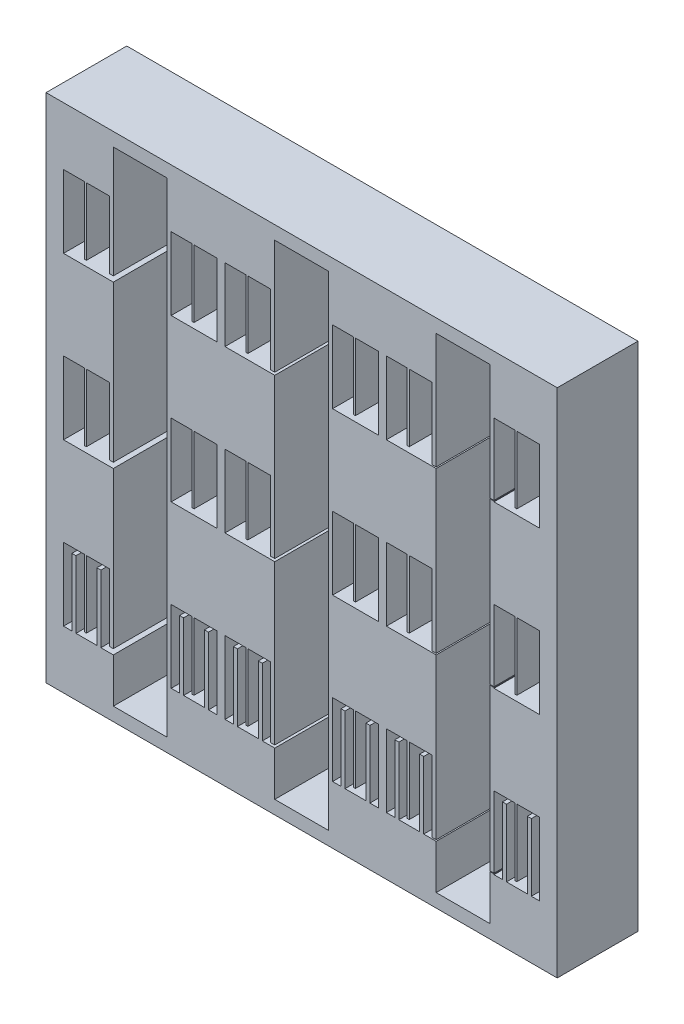
SolidWorks part; units mm, degrees
material "ABS"
ref_plane "Front Plane" through (0, 0, 0) normal (0, 0, 1) x (1, 0, 0)
ref_plane "Top Plane" through (0, 0, 0) normal (0, 1, 0) x (1, 0, 0)
ref_plane "Right Plane" through (0, 0, 0) normal (1, 0, 0) x (0, 0, -1)
sketch "Sketch1" plane through (0, 0, 0) normal (0, 0, 1) x (1, 0, 0)
  line L1 (-95, -95) -> (95, -95)
  line L2 (-95, -95) -> (-95, 95)
  line L3 (-95, 95) -> (95, 95)
  line L4 (95, -95) -> (95, 95)
  line L5 (0, 95) -> (0, -95) construction
  line L6 (-95, 0) -> (95, 0) construction
  point P16 (0, 0)
extrude "Boss-Extrude1" add sketch "Sketch1" against normal blind 30
sketch "Sketch2" plane through (0, 0, 0) normal (0, 0, 1) x (1, 0, 0)
  line L1 (-70, -90) -> (-50, -90)
  line L2 (-70, -90) -> (-70, 90)
  line L3 (-70, 90) -> (-50, 90)
  line L4 (-50, -90) -> (-50, 90)
  line L5 (-60, 90) -> (-60, -90) construction
  line L6 (-70, 0) -> (-50, 0) construction
  line L7 (-10, -90) -> (10, -90)
  line L8 (-10, -90) -> (-10, 90)
  line L9 (-10, 90) -> (10, 90)
  line L10 (10, -90) -> (10, 90)
  line L11 (0, 90) -> (0, -90) construction
  line L12 (-10, 0) -> (10, 0) construction
  line L13 (50, -90) -> (70, -90)
  line L14 (50, -90) -> (50, 90)
  line L15 (50, 90) -> (70, 90)
  line L16 (70, -90) -> (70, 90)
  line L17 (60, 90) -> (60, -90) construction
  line L18 (50, 0) -> (70, 0) construction
  point P16 (-60, 0)
  point P25 (0, 0)
  point P34 (60, 0)
extrude "Cut-Extrude1" cut sketch "Sketch2" against normal through all
sketch "Sketch3" plane through (0, 0, 0) normal (0, 0, 1) x (1, 0, 0)
  line L1 (-88.5, -73.5) -> (-71.5, -73.5)
  line L2 (-88.5, -73.5) -> (-88.5, -46.5)
  line L3 (-88.5, -46.5) -> (-71.5, -46.5)
  line L4 (-71.5, -73.5) -> (-71.5, -46.5)
  line L5 (-80, -46.5) -> (-80, -73.5) construction
  line L6 (-88.5, -60) -> (-71.5, -60) construction
  line L7 (-48.5, -73.5) -> (-31.5, -73.5)
  line L8 (-48.5, -73.5) -> (-48.5, -46.5)
  line L9 (-48.5, -46.5) -> (-31.5, -46.5)
  line L10 (-31.5, -73.5) -> (-31.5, -46.5)
  line L11 (-40, -46.5) -> (-40, -73.5) construction
  line L12 (-48.5, -60) -> (-31.5, -60) construction
  line L13 (-28.5, -73.5) -> (-11.5, -73.5)
  line L14 (-28.5, -73.5) -> (-28.5, -46.5)
  line L15 (-28.5, -46.5) -> (-11.5, -46.5)
  line L16 (-11.5, -73.5) -> (-11.5, -46.5)
  line L17 (-20, -46.5) -> (-20, -73.5) construction
  line L18 (-28.5, -60) -> (-11.5, -60) construction
  line L19 (11.5, -73.5) -> (28.5, -73.5)
  line L20 (11.5, -73.5) -> (11.5, -46.5)
  line L21 (11.5, -46.5) -> (28.5, -46.5)
  line L22 (28.5, -73.5) -> (28.5, -46.5)
  line L23 (20, -46.5) -> (20, -73.5) construction
  line L24 (11.5, -60) -> (28.5, -60) construction
  line L25 (31.5, -73.5) -> (48.5, -73.5)
  line L26 (31.5, -73.5) -> (31.5, -46.5)
  line L27 (31.5, -46.5) -> (48.5, -46.5)
  line L28 (48.5, -73.5) -> (48.5, -46.5)
  line L29 (40, -46.5) -> (40, -73.5) construction
  line L30 (31.5, -60) -> (48.5, -60) construction
  line L31 (71.5, -73.5) -> (88.5, -73.5)
  line L32 (71.5, -73.5) -> (71.5, -46.5)
  line L33 (71.5, -46.5) -> (88.5, -46.5)
  line L34 (88.5, -73.5) -> (88.5, -46.5)
  line L35 (80, -46.5) -> (80, -73.5) construction
  line L36 (71.5, -60) -> (88.5, -60) construction
  line L37 (-88.5, -13.5) -> (-71.5, -13.5)
  line L38 (-88.5, -13.5) -> (-88.5, 13.5)
  line L39 (-88.5, 13.5) -> (-71.5, 13.5)
  line L40 (-71.5, -13.5) -> (-71.5, 13.5)
  line L41 (-80, 13.5) -> (-80, -13.5) construction
  line L42 (-88.5, 0) -> (-71.5, 0) construction
  line L43 (-48.5, -13.5) -> (-31.5, -13.5)
  line L44 (-48.5, -13.5) -> (-48.5, 13.5)
  line L45 (-48.5, 13.5) -> (-31.5, 13.5)
  line L46 (-31.5, -13.5) -> (-31.5, 13.5)
  line L47 (-40, 13.5) -> (-40, -13.5) construction
  line L48 (-48.5, 0) -> (-31.5, 0) construction
  line L49 (-28.5, -13.5) -> (-11.5, -13.5)
  line L50 (-28.5, -13.5) -> (-28.5, 13.5)
  line L51 (-28.5, 13.5) -> (-11.5, 13.5)
  line L52 (-11.5, -13.5) -> (-11.5, 13.5)
  line L53 (-20, 13.5) -> (-20, -13.5) construction
  line L54 (-28.5, 0) -> (-11.5, 0) construction
  line L55 (11.5, -13.5) -> (28.5, -13.5)
  line L56 (11.5, -13.5) -> (11.5, 13.5)
  line L57 (11.5, 13.5) -> (28.5, 13.5)
  line L58 (28.5, -13.5) -> (28.5, 13.5)
  line L59 (20, 13.5) -> (20, -13.5) construction
  line L60 (11.5, 0) -> (28.5, 0) construction
  line L61 (31.5, -13.5) -> (48.5, -13.5)
  line L62 (31.5, -13.5) -> (31.5, 13.5)
  line L63 (31.5, 13.5) -> (48.5, 13.5)
  line L64 (48.5, -13.5) -> (48.5, 13.5)
  line L65 (40, 13.5) -> (40, -13.5) construction
  line L66 (31.5, 0) -> (48.5, 0) construction
  line L67 (71.5, -13.5) -> (88.5, -13.5)
  line L68 (71.5, -13.5) -> (71.5, 13.5)
  line L69 (71.5, 13.5) -> (88.5, 13.5)
  line L70 (88.5, -13.5) -> (88.5, 13.5)
  line L71 (80, 13.5) -> (80, -13.5) construction
  line L72 (71.5, 0) -> (88.5, 0) construction
  line L73 (-88.5, 46.5) -> (-71.5, 46.5)
  line L74 (-88.5, 46.5) -> (-88.5, 73.5)
  line L75 (-88.5, 73.5) -> (-71.5, 73.5)
  line L76 (-71.5, 46.5) -> (-71.5, 73.5)
  line L77 (-80, 73.5) -> (-80, 46.5) construction
  line L78 (-88.5, 60) -> (-71.5, 60) construction
  line L79 (-48.5, 46.5) -> (-31.5, 46.5)
  line L80 (-48.5, 46.5) -> (-48.5, 73.5)
  line L81 (-48.5, 73.5) -> (-31.5, 73.5)
  line L82 (-31.5, 46.5) -> (-31.5, 73.5)
  line L83 (-40, 73.5) -> (-40, 46.5) construction
  line L84 (-48.5, 60) -> (-31.5, 60) construction
  line L85 (-28.5, 46.5) -> (-11.5, 46.5)
  line L86 (-28.5, 46.5) -> (-28.5, 73.5)
  line L87 (-28.5, 73.5) -> (-11.5, 73.5)
  line L88 (-11.5, 46.5) -> (-11.5, 73.5)
  line L89 (-20, 73.5) -> (-20, 46.5) construction
  line L90 (-28.5, 60) -> (-11.5, 60) construction
  line L91 (11.5, 46.5) -> (28.5, 46.5)
  line L92 (11.5, 46.5) -> (11.5, 73.5)
  line L93 (11.5, 73.5) -> (28.5, 73.5)
  line L94 (28.5, 46.5) -> (28.5, 73.5)
  line L95 (20, 73.5) -> (20, 46.5) construction
  line L96 (11.5, 60) -> (28.5, 60) construction
  line L97 (31.5, 46.5) -> (48.5, 46.5)
  line L98 (31.5, 46.5) -> (31.5, 73.5)
  line L99 (31.5, 73.5) -> (48.5, 73.5)
  line L100 (48.5, 46.5) -> (48.5, 73.5)
  line L101 (40, 73.5) -> (40, 46.5) construction
  line L102 (31.5, 60) -> (48.5, 60) construction
  line L103 (71.5, 46.5) -> (88.5, 46.5)
  line L104 (71.5, 46.5) -> (71.5, 73.5)
  line L105 (71.5, 73.5) -> (88.5, 73.5)
  line L106 (88.5, 46.5) -> (88.5, 73.5)
  line L107 (80, 73.5) -> (80, 46.5) construction
  line L108 (71.5, 60) -> (88.5, 60) construction
  point P16 (-80, -60)
  point P25 (-40, -60)
  point P34 (-20, -60)
  point P43 (20, -60)
  point P52 (40, -60)
  point P61 (80, -60)
  point P70 (-80, 0)
  point P79 (-40, 0)
  point P88 (-20, 0)
  point P97 (20, 0)
  point P106 (40, 0)
  point P115 (80, 0)
  point P124 (-80, 60)
  point P133 (-40, 60)
  point P142 (-20, 60)
  point P151 (20, 60)
  point P160 (40, 60)
  point P169 (80, 60)
extrude "Cut-Extrude2" cut sketch "Sketch3" against normal blind 28.5
sketch "Sketch4" plane through (0, 0, 0) normal (0, 0, 1) x (1, 0, 0)
  line L0 (-88.5, -73.5) -> (-71.5, -73.5) construction
  line L1 (-76.125, -73.5) -> (-74.625, -73.5)
  line L2 (-76.125, -73.5) -> (-76.125, -48.5)
  line L3 (-76.125, -48.5) -> (-74.625, -48.5)
  line L4 (-74.625, -73.5) -> (-74.625, -48.5)
  line L5 (-75.375, -48.5) -> (-75.375, -73.5) construction
  line L6 (-76.125, -61) -> (-74.625, -61) construction
  line L7 (-71.5, -46.5) -> (-88.5, -46.5) construction
  line L8 (-80.75, -71.5) -> (-80, -71.5)
  line L9 (-80.75, -71.5) -> (-80.75, -46.5)
  line L10 (-80.75, -46.5) -> (-80, -46.5)
  line L11 (-80, -71.5) -> (-80, -46.5)
  line L12 (-80.375, -46.5) -> (-80.375, -71.5) construction
  line L13 (-80.75, -59) -> (-80, -59) construction
  line L14 (-48.5, -73.5) -> (-31.5, -73.5) construction
  line L15 (-85.375, -73.5) -> (-83.875, -73.5)
  line L16 (-85.375, -73.5) -> (-85.375, -48.5)
  line L17 (-85.375, -48.5) -> (-83.875, -48.5)
  line L18 (-83.875, -73.5) -> (-83.875, -48.5)
  line L19 (-84.625, -48.5) -> (-84.625, -73.5) construction
  line L20 (-85.375, -61) -> (-83.875, -61) construction
  line L21 (-45.375, -73.5) -> (-43.875, -73.5)
  line L22 (-45.375, -73.5) -> (-45.375, -48.5)
  line L23 (-45.375, -48.5) -> (-43.875, -48.5)
  line L24 (-43.875, -73.5) -> (-43.875, -48.5)
  line L25 (-44.625, -48.5) -> (-44.625, -73.5) construction
  line L26 (-45.375, -61) -> (-43.875, -61) construction
  line L27 (-31.5, -46.5) -> (-48.5, -46.5) construction
  line L28 (-40.75, -71.5) -> (-40, -71.5)
  line L29 (-40.75, -71.5) -> (-40.75, -46.5)
  line L30 (-40.75, -46.5) -> (-40, -46.5)
  line L31 (-40, -71.5) -> (-40, -46.5)
  line L32 (-40.375, -46.5) -> (-40.375, -71.5) construction
  line L33 (-40.75, -59) -> (-40, -59) construction
  line L34 (-28.5, -73.5) -> (-11.5, -73.5) construction
  line L35 (-36.125, -73.5) -> (-34.625, -73.5)
  line L36 (-36.125, -73.5) -> (-36.125, -48.5)
  line L37 (-36.125, -48.5) -> (-34.625, -48.5)
  line L38 (-34.625, -73.5) -> (-34.625, -48.5)
  line L39 (-35.375, -48.5) -> (-35.375, -73.5) construction
  line L40 (-36.125, -61) -> (-34.625, -61) construction
  line L41 (-16.125, -73.5) -> (-14.625, -73.5)
  line L42 (-16.125, -73.5) -> (-16.125, -48.5)
  line L43 (-16.125, -48.5) -> (-14.625, -48.5)
  line L44 (-14.625, -73.5) -> (-14.625, -48.5)
  line L45 (-15.375, -48.5) -> (-15.375, -73.5) construction
  line L46 (-16.125, -61) -> (-14.625, -61) construction
  line L47 (-11.5, -46.5) -> (-28.5, -46.5) construction
  line L48 (-20.75, -71.5) -> (-20, -71.5)
  line L49 (-20.75, -71.5) -> (-20.75, -46.5)
  line L50 (-20.75, -46.5) -> (-20, -46.5)
  line L51 (-20, -71.5) -> (-20, -46.5)
  line L52 (-20.375, -46.5) -> (-20.375, -71.5) construction
  line L53 (-20.75, -59) -> (-20, -59) construction
  line L54 (11.5, -73.5) -> (28.5, -73.5) construction
  line L55 (-25.375, -73.5) -> (-23.875, -73.5)
  line L56 (-25.375, -73.5) -> (-25.375, -48.5)
  line L57 (-25.375, -48.5) -> (-23.875, -48.5)
  line L58 (-23.875, -73.5) -> (-23.875, -48.5)
  line L59 (-24.625, -48.5) -> (-24.625, -73.5) construction
  line L60 (-25.375, -61) -> (-23.875, -61) construction
  line L61 (14.625, -73.5) -> (16.125, -73.5)
  line L62 (14.625, -73.5) -> (14.625, -48.5)
  line L63 (14.625, -48.5) -> (16.125, -48.5)
  line L64 (16.125, -73.5) -> (16.125, -48.5)
  line L65 (15.375, -48.5) -> (15.375, -73.5) construction
  line L66 (14.625, -61) -> (16.125, -61) construction
  line L67 (28.5, -46.5) -> (11.5, -46.5) construction
  line L68 (19.25, -71.5) -> (20, -71.5)
  line L69 (19.25, -71.5) -> (19.25, -46.5)
  line L70 (19.25, -46.5) -> (20, -46.5)
  line L71 (20, -71.5) -> (20, -46.5)
  line L72 (19.625, -46.5) -> (19.625, -71.5) construction
  line L73 (19.25, -59) -> (20, -59) construction
  line L74 (31.5, -73.5) -> (48.5, -73.5) construction
  line L75 (23.875, -73.5) -> (25.375, -73.5)
  line L76 (23.875, -73.5) -> (23.875, -48.5)
  line L77 (23.875, -48.5) -> (25.375, -48.5)
  line L78 (25.375, -73.5) -> (25.375, -48.5)
  line L79 (24.625, -48.5) -> (24.625, -73.5) construction
  line L80 (23.875, -61) -> (25.375, -61) construction
  line L81 (43.875, -73.5) -> (45.375, -73.5)
  line L82 (43.875, -73.5) -> (43.875, -48.5)
  line L83 (43.875, -48.5) -> (45.375, -48.5)
  line L84 (45.375, -73.5) -> (45.375, -48.5)
  line L85 (44.625, -48.5) -> (44.625, -73.5) construction
  line L86 (43.875, -61) -> (45.375, -61) construction
  line L87 (48.5, -46.5) -> (31.5, -46.5) construction
  line L88 (39.25, -71.5) -> (40, -71.5)
  line L89 (39.25, -71.5) -> (39.25, -46.5)
  line L90 (39.25, -46.5) -> (40, -46.5)
  line L91 (40, -71.5) -> (40, -46.5)
  line L92 (39.625, -46.5) -> (39.625, -71.5) construction
  line L93 (39.25, -59) -> (40, -59) construction
  line L94 (71.5, -73.5) -> (88.5, -73.5) construction
  line L95 (34.625, -73.5) -> (36.125, -73.5)
  line L96 (34.625, -73.5) -> (34.625, -48.5)
  line L97 (34.625, -48.5) -> (36.125, -48.5)
  line L98 (36.125, -73.5) -> (36.125, -48.5)
  line L99 (35.375, -48.5) -> (35.375, -73.5) construction
  line L100 (34.625, -61) -> (36.125, -61) construction
  line L101 (74.625, -73.5) -> (76.125, -73.5)
  line L102 (74.625, -73.5) -> (74.625, -48.5)
  line L103 (74.625, -48.5) -> (76.125, -48.5)
  line L104 (76.125, -73.5) -> (76.125, -48.5)
  line L105 (75.375, -48.5) -> (75.375, -73.5) construction
  line L106 (74.625, -61) -> (76.125, -61) construction
  line L107 (88.5, -46.5) -> (71.5, -46.5) construction
  line L108 (79.25, -71.5) -> (80, -71.5)
  line L109 (79.25, -71.5) -> (79.25, -46.5)
  line L110 (79.25, -46.5) -> (80, -46.5)
  line L111 (80, -71.5) -> (80, -46.5)
  line L112 (79.625, -46.5) -> (79.625, -71.5) construction
  line L113 (79.25, -59) -> (80, -59) construction
  line L114 (-71.5, 13.5) -> (-88.5, 13.5) construction
  line L115 (83.875, -73.5) -> (85.375, -73.5)
  line L116 (83.875, -73.5) -> (83.875, -48.5)
  line L117 (83.875, -48.5) -> (85.375, -48.5)
  line L118 (85.375, -73.5) -> (85.375, -48.5)
  line L119 (84.625, -48.5) -> (84.625, -73.5) construction
  line L120 (83.875, -61) -> (85.375, -61) construction
  line L121 (-80.75, -11.5) -> (-80, -11.5)
  line L122 (-80.75, -11.5) -> (-80.75, 13.5)
  line L123 (-80.75, 13.5) -> (-80, 13.5)
  line L124 (-80, -11.5) -> (-80, 13.5)
  line L125 (-80.375, 13.5) -> (-80.375, -11.5) construction
  line L126 (-80.75, 1) -> (-80, 1) construction
  line L127 (-31.5, 13.5) -> (-48.5, 13.5) construction
  line L128 (-40.75, -11.5) -> (-40, -11.5)
  line L129 (-40.75, -11.5) -> (-40.75, 13.5)
  line L130 (-40.75, 13.5) -> (-40, 13.5)
  line L131 (-40, -11.5) -> (-40, 13.5)
  line L132 (-40.375, 13.5) -> (-40.375, -11.5) construction
  line L133 (-40.75, 1) -> (-40, 1) construction
  line L134 (-11.5, 13.5) -> (-28.5, 13.5) construction
  line L135 (-20.75, -11.5) -> (-20, -11.5)
  line L136 (-20.75, -11.5) -> (-20.75, 13.5)
  line L137 (-20.75, 13.5) -> (-20, 13.5)
  line L138 (-20, -11.5) -> (-20, 13.5)
  line L139 (-20.375, 13.5) -> (-20.375, -11.5) construction
  line L140 (-20.75, 1) -> (-20, 1) construction
  line L141 (28.5, 13.5) -> (11.5, 13.5) construction
  line L142 (19.25, -11.5) -> (20, -11.5)
  line L143 (19.25, -11.5) -> (19.25, 13.5)
  line L144 (19.25, 13.5) -> (20, 13.5)
  line L145 (20, -11.5) -> (20, 13.5)
  line L146 (19.625, 13.5) -> (19.625, -11.5) construction
  line L147 (19.25, 1) -> (20, 1) construction
  line L148 (48.5, 13.5) -> (31.5, 13.5) construction
  line L149 (39.25, -11.5) -> (40, -11.5)
  line L150 (39.25, -11.5) -> (39.25, 13.5)
  line L151 (39.25, 13.5) -> (40, 13.5)
  line L152 (40, -11.5) -> (40, 13.5)
  line L153 (39.625, 13.5) -> (39.625, -11.5) construction
  line L154 (39.25, 1) -> (40, 1) construction
  line L155 (88.5, 13.5) -> (71.5, 13.5) construction
  line L156 (79.25, -11.5) -> (80, -11.5)
  line L157 (79.25, -11.5) -> (79.25, 13.5)
  line L158 (79.25, 13.5) -> (80, 13.5)
  line L159 (80, -11.5) -> (80, 13.5)
  line L160 (79.625, 13.5) -> (79.625, -11.5) construction
  line L161 (79.25, 1) -> (80, 1) construction
  line L162 (-71.5, 73.5) -> (-88.5, 73.5) construction
  line L163 (-80.75, 48.5) -> (-80, 48.5)
  line L164 (-80.75, 48.5) -> (-80.75, 73.5)
  line L165 (-80.75, 73.5) -> (-80, 73.5)
  line L166 (-80, 48.5) -> (-80, 73.5)
  line L167 (-80.375, 73.5) -> (-80.375, 48.5) construction
  line L168 (-80.75, 61) -> (-80, 61) construction
  line L169 (-31.5, 73.5) -> (-48.5, 73.5) construction
  line L170 (-40.75, 48.5) -> (-40, 48.5)
  line L171 (-40.75, 48.5) -> (-40.75, 73.5)
  line L172 (-40.75, 73.5) -> (-40, 73.5)
  line L173 (-40, 48.5) -> (-40, 73.5)
  line L174 (-40.375, 73.5) -> (-40.375, 48.5) construction
  line L175 (-40.75, 61) -> (-40, 61) construction
  line L176 (-11.5, 73.5) -> (-28.5, 73.5) construction
  line L177 (-20.75, 48.5) -> (-20, 48.5)
  line L178 (-20.75, 48.5) -> (-20.75, 73.5)
  line L179 (-20.75, 73.5) -> (-20, 73.5)
  line L180 (-20, 48.5) -> (-20, 73.5)
  line L181 (-20.375, 73.5) -> (-20.375, 48.5) construction
  line L182 (-20.75, 61) -> (-20, 61) construction
  line L183 (28.5, 73.5) -> (11.5, 73.5) construction
  line L184 (19.25, 48.5) -> (20, 48.5)
  line L185 (19.25, 48.5) -> (19.25, 73.5)
  line L186 (19.25, 73.5) -> (20, 73.5)
  line L187 (20, 48.5) -> (20, 73.5)
  line L188 (19.625, 73.5) -> (19.625, 48.5) construction
  line L189 (19.25, 61) -> (20, 61) construction
  line L190 (48.5, 73.5) -> (31.5, 73.5) construction
  line L191 (39.25, 48.5) -> (40, 48.5)
  line L192 (39.25, 48.5) -> (39.25, 73.5)
  line L193 (39.25, 73.5) -> (40, 73.5)
  line L194 (40, 48.5) -> (40, 73.5)
  line L195 (39.625, 73.5) -> (39.625, 48.5) construction
  line L196 (39.25, 61) -> (40, 61) construction
  line L197 (88.5, 73.5) -> (71.5, 73.5) construction
  line L198 (79.25, 48.5) -> (80, 48.5)
  line L199 (79.25, 48.5) -> (79.25, 73.5)
  line L200 (79.25, 73.5) -> (80, 73.5)
  line L201 (80, 48.5) -> (80, 73.5)
  line L202 (79.625, 73.5) -> (79.625, 48.5) construction
  line L203 (79.25, 61) -> (80, 61) construction
  point P16 (-75.375, -61)
  point P31 (-80.375, -59)
  point P38 (-84.625, -61)
  point P47 (-44.625, -61)
  point P62 (-40.375, -59)
  point P69 (-35.375, -61)
  point P78 (-15.375, -61)
  point P93 (-20.375, -59)
  point P100 (-24.625, -61)
  point P109 (15.375, -61)
  point P124 (19.625, -59)
  point P131 (24.625, -61)
  point P140 (44.625, -61)
  point P155 (39.625, -59)
  point P162 (35.375, -61)
  point P171 (75.375, -61)
  point P186 (79.625, -59)
  point P193 (84.625, -61)
  point P206 (-80.375, 1)
  point P217 (-40.375, 1)
  point P228 (-20.375, 1)
  point P239 (19.625, 1)
  point P250 (39.625, 1)
  point P261 (79.625, 1)
  point P272 (-80.375, 61)
  point P283 (-40.375, 61)
  point P294 (-20.375, 61)
  point P305 (19.625, 61)
  point P316 (39.625, 61)
  point P327 (79.625, 61)
extrude "Boss-Extrude2" add sketch "Sketch4" against normal blind 28.5
sketch "Sketch5" plane through (0, 0, 0) normal (0, 0, 1) x (1, 0, 0)
  line L0 (-70, 90) -> (-70, -90) construction
  line L1 (-71.5, -73.5) -> (-70, -73.5)
  line L2 (-71.5, -73.5) -> (-71.5, -71.5)
  line L3 (-71.5, -71.5) -> (-70, -71.5)
  line L4 (-70, -73.5) -> (-70, -71.5)
  line L5 (-70.75, -71.5) -> (-70.75, -73.5) construction
  line L6 (-71.5, -72.5) -> (-70, -72.5) construction
  line L7 (-10, 90) -> (-10, -90) construction
  line L8 (-11.5, -73.5) -> (-10, -73.5)
  line L9 (-11.5, -73.5) -> (-11.5, -72.5)
  line L10 (-11.5, -72.5) -> (-10, -72.5)
  line L11 (-10, -73.5) -> (-10, -72.5)
  line L12 (-10.75, -72.5) -> (-10.75, -73.5) construction
  line L13 (-11.5, -73) -> (-10, -73) construction
  line L14 (50, 90) -> (50, -90) construction
  line L15 (48.5, -73.5) -> (50, -73.5)
  line L16 (48.5, -73.5) -> (48.5, -73)
  line L17 (48.5, -73) -> (50, -73)
  line L18 (50, -73.5) -> (50, -73)
  line L19 (49.25, -73) -> (49.25, -73.5) construction
  line L20 (48.5, -73.25) -> (50, -73.25) construction
  line L21 (70, -90) -> (70, 90) construction
  line L22 (70, -73.25) -> (71.5, -73.25)
  line L23 (70, -73.25) -> (70, -73)
  line L24 (70, -73) -> (71.5, -73)
  line L25 (71.5, -73.25) -> (71.5, -73)
  line L26 (70.75, -73) -> (70.75, -73.25) construction
  line L27 (70, -73.125) -> (71.5, -73.125) construction
  line L28 (71.5, -46.5) -> (71.5, -73.5) construction
  line L29 (71.5, 13.5) -> (71.5, -13.5) construction
  line L30 (-71.5, -13.5) -> (-70, -13.5)
  line L31 (-71.5, -13.5) -> (-71.5, -11.5)
  line L32 (-71.5, -11.5) -> (-70, -11.5)
  line L33 (-70, -13.5) -> (-70, -11.5)
  line L34 (-70.75, -11.5) -> (-70.75, -13.5) construction
  line L35 (-71.5, -12.5) -> (-70, -12.5) construction
  line L36 (-11.5, -13.5) -> (-10, -13.5)
  line L37 (-11.5, -13.5) -> (-11.5, -12.5)
  line L38 (-11.5, -12.5) -> (-10, -12.5)
  line L39 (-10, -13.5) -> (-10, -12.5)
  line L40 (-10.75, -12.5) -> (-10.75, -13.5) construction
  line L41 (-11.5, -13) -> (-10, -13) construction
  line L42 (48.5, -13.5) -> (50, -13.5)
  line L43 (48.5, -13.5) -> (48.5, -13)
  line L44 (48.5, -13) -> (50, -13)
  line L45 (50, -13.5) -> (50, -13)
  line L46 (49.25, -13) -> (49.25, -13.5) construction
  line L47 (48.5, -13.25) -> (50, -13.25) construction
  line L48 (70, -13.25) -> (71.5, -13.25)
  line L49 (70, -13.25) -> (70, -13)
  line L50 (70, -13) -> (71.5, -13)
  line L51 (71.5, -13.25) -> (71.5, -13)
  line L52 (70.75, -13) -> (70.75, -13.25) construction
  line L53 (70, -13.125) -> (71.5, -13.125) construction
  line L54 (71.5, 73.5) -> (71.5, 46.5) construction
  line L55 (-71.5, 46.5) -> (-70, 46.5)
  line L56 (-71.5, 46.5) -> (-71.5, 48.5)
  line L57 (-71.5, 48.5) -> (-70, 48.5)
  line L58 (-70, 46.5) -> (-70, 48.5)
  line L59 (-70.75, 48.5) -> (-70.75, 46.5) construction
  line L60 (-71.5, 47.5) -> (-70, 47.5) construction
  line L61 (-11.5, 46.5) -> (-10, 46.5)
  line L62 (-11.5, 46.5) -> (-11.5, 47.5)
  line L63 (-11.5, 47.5) -> (-10, 47.5)
  line L64 (-10, 46.5) -> (-10, 47.5)
  line L65 (-10.75, 47.5) -> (-10.75, 46.5) construction
  line L66 (-11.5, 47) -> (-10, 47) construction
  line L67 (48.5, 46.5) -> (50, 46.5)
  line L68 (48.5, 46.5) -> (48.5, 47)
  line L69 (48.5, 47) -> (50, 47)
  line L70 (50, 46.5) -> (50, 47)
  line L71 (49.25, 47) -> (49.25, 46.5) construction
  line L72 (48.5, 46.75) -> (50, 46.75) construction
  line L73 (70, 46.75) -> (71.5, 46.75)
  line L74 (70, 46.75) -> (70, 47)
  line L75 (70, 47) -> (71.5, 47)
  line L76 (71.5, 46.75) -> (71.5, 47)
  line L77 (70.75, 47) -> (70.75, 46.75) construction
  line L78 (70, 46.875) -> (71.5, 46.875) construction
  point P20 (-70.75, -72.5)
  point P32 (-10.75, -73)
  point P44 (49.25, -73.25)
  point P56 (70.75, -73.125)
  point P69 (-70.75, -12.5)
  point P79 (-10.75, -13)
  point P89 (49.25, -13.25)
  point P99 (70.75, -13.125)
  point P110 (-70.75, 47.5)
  point P120 (-10.75, 47)
  point P130 (49.25, 46.75)
  point P140 (70.75, 46.875)
extrude "Cut-Extrude3" cut sketch "Sketch5" against normal blind 28.5
